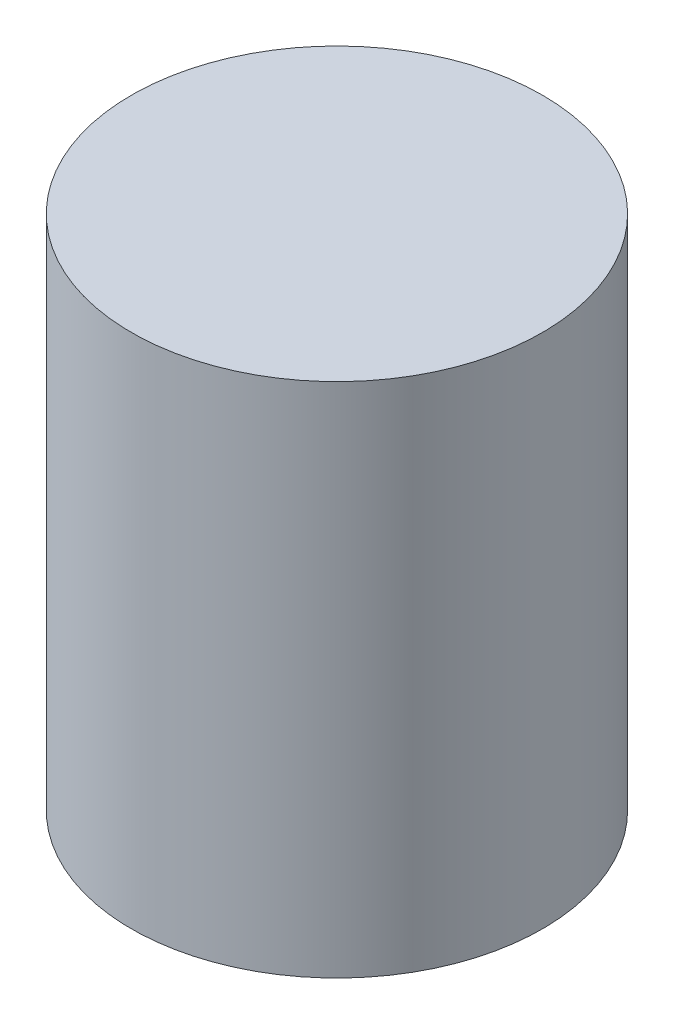
SolidWorks part; units mm, degrees
ref_plane "Front Plane" through (0, 0, 0) normal (0, 0, 1) x (1, 0, 0)
ref_plane "Top Plane" through (0, 0, 0) normal (0, 1, 0) x (1, 0, 0)
ref_plane "Right Plane" through (0, 0, 0) normal (1, 0, 0) x (0, 0, -1)
sketch "Sketch1" plane through (0, 0, 0) normal (0, 1, 0) x (1, 0, 0)
  circle A0 centre (0, 0) radius 43.3758
extrude "Boss-Extrude1" add sketch "Sketch1" along normal blind 109
